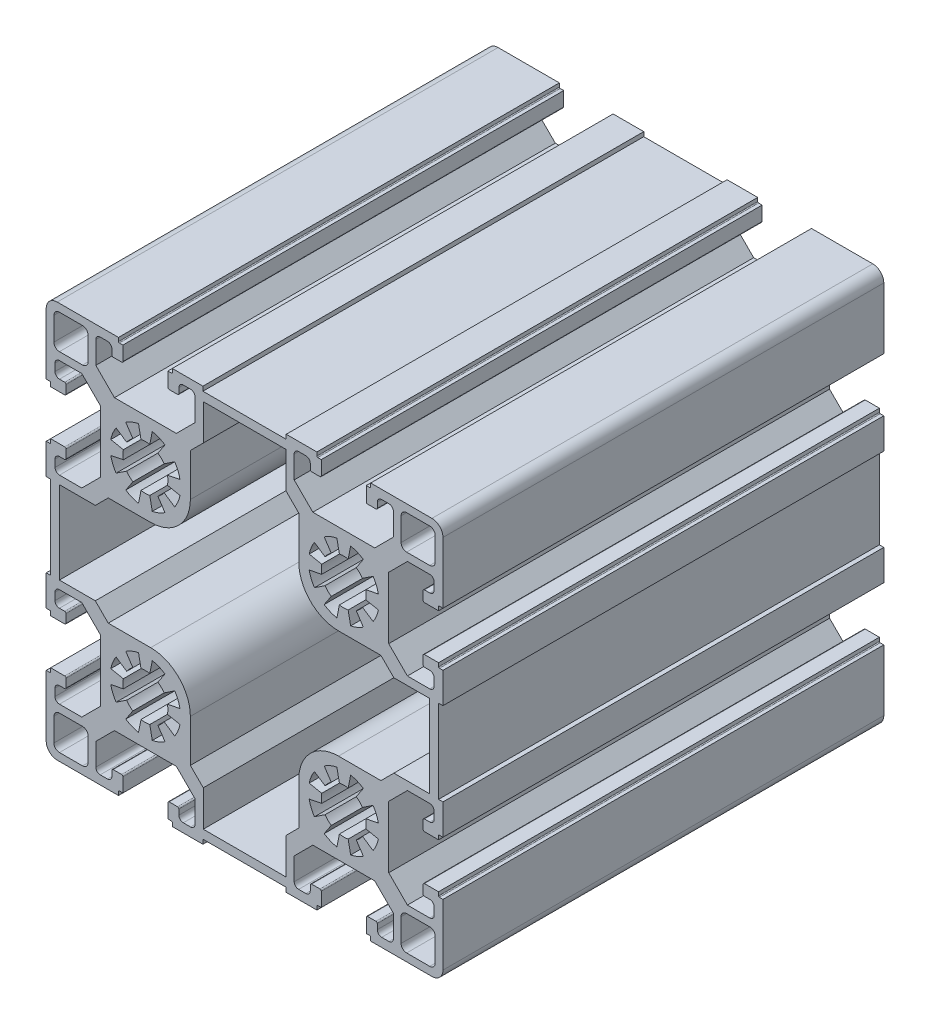
SolidWorks part; units mm, degrees
ref_plane "前视基准面" through (0, 0, 0) normal (0, 0, 1) x (1, 0, 0)
ref_plane "上视基准面" through (0, 0, 0) normal (0, 1, 0) x (1, 0, 0)
ref_plane "右视基准面" through (0, 0, 0) normal (1, 0, 0) x (0, 0, -1)
sketch "草图1" plane through (0, 0, 0) normal (0, 0, 1) x (1, 0, 0)
  line L0 (-29.0828, 43.3346) -> (-42.9828, 43.3346)
  line L1 (-45.4828, 40.8346) -> (-45.4828, 26.9346)
  line L2 (-28.0828, 42.3346) -> (-28.0828, 39.1346)
  line L3 (-28.3828, 38.8346) -> (-30.2828, 38.8346)
  line L4 (-30.5828, 39.1346) -> (-30.5828, 40.3346)
  line L5 (-31.5828, 41.3346) -> (-33.2328, 41.3346)
  line L6 (-34.2328, 40.3346) -> (-34.2328, 35.2666)
  line L7 (-42.4828, 33.8346) -> (-37.2328, 33.8346)
  line L8 (-35.9828, 35.0846) -> (-35.9828, 40.3346)
  line L9 (-37.2328, 41.5846) -> (-42.4828, 41.5846)
  line L10 (-43.7328, 40.3346) -> (-43.7328, 35.0846)
  line L11 (-37.4148, 32.0846) -> (-42.4828, 32.0846)
  line L12 (-43.4828, 31.0846) -> (-43.4828, 29.4346)
  line L13 (-42.4828, 28.4346) -> (-41.2828, 28.4346)
  line L14 (-40.9828, 28.1346) -> (-40.9828, 26.2346)
  line L15 (-41.2828, 25.9346) -> (-44.4828, 25.9346)
  line L16 (-28.0828, 42.3346) -> (-28.8828, 42.3346)
  line L17 (-29.0828, 42.5346) -> (-29.0828, 43.3346)
  line L18 (-45.4828, 26.9346) -> (-44.6828, 26.9346)
  line L19 (-44.4828, 26.7346) -> (-44.4828, 25.9346)
  line L20 (-17.8828, 42.3346) -> (-17.8828, 39.1346)
  line L21 (-17.5828, 38.8346) -> (-15.6828, 38.8346)
  line L22 (-15.3828, 39.1346) -> (-15.3828, 40.3346)
  line L23 (-14.3828, 41.3346) -> (-12.7328, 41.3346)
  line L24 (-11.7328, 40.3346) -> (-11.7328, 35.2666)
  line L25 (-17.8828, 42.3346) -> (-17.0828, 42.3346)
  line L26 (-16.8828, 42.5346) -> (-16.8828, 43.3346)
  line L27 (-37.4148, 9.5846) -> (-42.4828, 9.5846)
  line L28 (-43.4828, 10.5846) -> (-43.4828, 12.2346)
  line L29 (-42.4828, 13.2346) -> (-41.2828, 13.2346)
  line L30 (-40.9828, 13.5346) -> (-40.9828, 15.4346)
  line L31 (-41.2828, 15.7346) -> (-44.4828, 15.7346)
  line L32 (-45.4828, 14.7346) -> (-44.6828, 14.7346)
  line L33 (-44.4828, 14.9346) -> (-44.4828, 15.7346)
  line L34 (-27.4274, 14.1828) -> (-25.8162, 16.5941)
  line L35 (-24.5435, 12.9883) -> (-23.9778, 15.8326)
  line L36 (-21.4221, 12.9883) -> (-21.9878, 15.8326)
  line L37 (-18.5382, 14.1828) -> (-20.1494, 16.5941)
  line L38 (-16.3311, 16.39) -> (-18.7423, 18.0012)
  line L39 (-15.1365, 19.2738) -> (-17.9808, 19.8396)
  line L40 (-15.1365, 22.3953) -> (-17.9808, 21.8295)
  line L41 (-16.3311, 25.2791) -> (-18.7423, 23.668)
  line L42 (-18.5382, 27.4863) -> (-20.1494, 25.0751)
  line L43 (-21.4221, 28.6809) -> (-21.9878, 25.8366)
  line L44 (-24.5435, 28.6809) -> (-23.9778, 25.8366)
  line L45 (-27.4274, 27.4863) -> (-25.8162, 25.0751)
  line L46 (-29.6346, 25.2791) -> (-27.2233, 23.668)
  line L47 (-30.8291, 22.3953) -> (-27.9848, 21.8295)
  line L48 (-30.8291, 19.2738) -> (-27.9848, 19.8396)
  line L49 (-29.6346, 16.39) -> (-27.2233, 18.0012)
  line L51 (-15.9648, 31.0346) -> (-30.0008, 31.0346)
  line L52 (-33.1828, 27.8526) -> (-33.1828, 13.8166)
  line L53 (-34.2328, 35.2666) -> (-30.0008, 31.0346)
  line L54 (-37.4148, 32.0846) -> (-33.1828, 27.8526)
  line L55 (-11.7328, 35.2666) -> (-15.9648, 31.0346)
  line L56 (-37.4148, 9.5846) -> (-33.1828, 13.8166)
  line L57 (16.9172, 42.3346) -> (16.9172, 39.1346)
  line L58 (16.6172, 38.8346) -> (14.7172, 38.8346)
  line L59 (14.4172, 39.1346) -> (14.4172, 40.3346)
  line L60 (13.4172, 41.3346) -> (11.7672, 41.3346)
  line L61 (10.7672, 40.3346) -> (10.7672, 35.2666)
  line L62 (16.9172, 42.3346) -> (16.1172, 42.3346)
  line L63 (15.9172, 42.5346) -> (15.9172, 43.3346)
  line L64 (28.1172, 43.3346) -> (42.0172, 43.3346)
  line L65 (44.5172, 40.8346) -> (44.5172, 26.9346)
  line L66 (27.1172, 42.3346) -> (27.1172, 39.1346)
  line L67 (27.4172, 38.8346) -> (29.3172, 38.8346)
  line L68 (29.6172, 39.1346) -> (29.6172, 40.3346)
  line L69 (30.6172, 41.3346) -> (32.2672, 41.3346)
  line L70 (33.2672, 40.3346) -> (33.2672, 35.2666)
  line L71 (41.5172, 33.8346) -> (36.2672, 33.8346)
  line L72 (36.2672, 41.5846) -> (41.5172, 41.5846)
  line L73 (42.7672, 40.3346) -> (42.7672, 35.0846)
  line L74 (36.4492, 32.0846) -> (41.5172, 32.0846)
  line L75 (42.5172, 31.0846) -> (42.5172, 29.4346)
  line L76 (41.5172, 28.4346) -> (40.3172, 28.4346)
  line L77 (40.0172, 28.1346) -> (40.0172, 26.2346)
  line L78 (40.3172, 25.9346) -> (43.5172, 25.9346)
  line L79 (27.1172, 42.3346) -> (27.9172, 42.3346)
  line L80 (28.1172, 42.5346) -> (28.1172, 43.3346)
  line L81 (44.5172, 26.9346) -> (43.7172, 26.9346)
  line L82 (43.5172, 26.7346) -> (43.5172, 25.9346)
  line L83 (36.4492, 9.5846) -> (41.5172, 9.5846)
  line L84 (42.5172, 10.5846) -> (42.5172, 12.2346)
  line L85 (41.5172, 13.2346) -> (40.3172, 13.2346)
  line L86 (40.0172, 13.5346) -> (40.0172, 15.4346)
  line L87 (40.3172, 15.7346) -> (43.5172, 15.7346)
  line L88 (44.5172, 14.7346) -> (43.7172, 14.7346)
  line L89 (43.5172, 14.9346) -> (43.5172, 15.7346)
  line L90 (17.5726, 14.1828) -> (19.1838, 16.5941)
  line L91 (20.4565, 12.9883) -> (21.0222, 15.8326)
  line L92 (23.5779, 12.9883) -> (23.0122, 15.8326)
  line L93 (26.4618, 14.1828) -> (24.8506, 16.5941)
  line L94 (28.6689, 16.39) -> (26.2577, 18.0012)
  line L95 (29.8635, 19.2738) -> (27.0192, 19.8396)
  line L96 (29.8635, 22.3953) -> (27.0192, 21.8295)
  line L97 (28.6689, 25.2791) -> (26.2577, 23.668)
  line L98 (26.4618, 27.4863) -> (24.8506, 25.0751)
  line L99 (23.5779, 28.6809) -> (23.0122, 25.8366)
  line L100 (20.4565, 28.6809) -> (21.0222, 25.8366)
  line L101 (17.5726, 27.4863) -> (19.1838, 25.0751)
  line L102 (15.3654, 25.2791) -> (17.7767, 23.668)
  line L103 (14.1709, 22.3953) -> (17.0152, 21.8295)
  line L104 (14.1709, 19.2738) -> (17.0152, 19.8396)
  line L105 (15.3654, 16.39) -> (17.7767, 18.0012)
  line L106 (32.2172, 13.8166) -> (32.2172, 27.8526)
  line L107 (29.0352, 31.0346) -> (14.9992, 31.0346)
  line L109 (10.7672, 35.2666) -> (14.9992, 31.0346)
  line L110 (33.2672, 35.2666) -> (29.0352, 31.0346)
  line L111 (36.4492, 32.0846) -> (32.2172, 27.8526)
  line L112 (36.4492, 9.5846) -> (32.2172, 13.8166)
  line L113 (-16.8828, 43.3346) -> (-9.9328, 43.3346)
  line L114 (-9.9328, 42.3346) -> (8.9672, 42.3346)
  line L115 (-9.8534, 40.3346) -> (8.8878, 40.3346)
  line L116 (-9.8534, 32.1962) -> (-12.7828, 29.2668)
  line L117 (15.9172, 43.3346) -> (8.9672, 43.3346)
  line L118 (8.8878, 32.1962) -> (11.8172, 29.2668)
  line L119 (8.9672, 42.3346) -> (8.9672, 43.3346)
  line L120 (-9.9328, 42.3346) -> (-9.9328, 43.3346)
  line L122 (11.8172, 29.2668) -> (11.8172, 19.6346)
  line L123 (-9.8534, 32.1962) -> (-9.8534, 40.3346)
  line L124 (8.8878, 32.1962) -> (8.8878, 40.3346)
  line L125 (-29.0828, -46.6654) -> (-42.9828, -46.6654)
  line L126 (-45.4828, -44.1654) -> (-45.4828, -30.2654)
  line L127 (-28.0828, -45.6654) -> (-28.0828, -42.4654)
  line L128 (-28.3828, -42.1654) -> (-30.2828, -42.1654)
  line L129 (-30.5828, -42.4654) -> (-30.5828, -43.6654)
  line L130 (-31.5828, -44.6654) -> (-33.2328, -44.6654)
  line L131 (-34.2328, -43.6654) -> (-34.2328, -38.5974)
  line L132 (-42.4828, -37.1654) -> (-37.2328, -37.1654)
  line L133 (-35.9828, -38.4154) -> (-35.9828, -43.6654)
  line L134 (-37.2328, -44.9154) -> (-42.4828, -44.9154)
  line L135 (-43.7328, -43.6654) -> (-43.7328, -38.4154)
  line L136 (-37.4148, -35.4154) -> (-42.4828, -35.4154)
  line L137 (-43.4828, -34.4154) -> (-43.4828, -32.7654)
  line L138 (-42.4828, -31.7654) -> (-41.2828, -31.7654)
  line L139 (-40.9828, -31.4654) -> (-40.9828, -29.5654)
  line L140 (-41.2828, -29.2654) -> (-44.4828, -29.2654)
  line L141 (-28.0828, -45.6654) -> (-28.8828, -45.6654)
  line L142 (-29.0828, -45.8654) -> (-29.0828, -46.6654)
  line L143 (-45.4828, -30.2654) -> (-44.6828, -30.2654)
  line L144 (-44.4828, -30.0654) -> (-44.4828, -29.2654)
  line L145 (-17.8828, -45.6654) -> (-17.8828, -42.4654)
  line L146 (-17.5828, -42.1654) -> (-15.6828, -42.1654)
  line L147 (-15.3828, -42.4654) -> (-15.3828, -43.6654)
  line L148 (-14.3828, -44.6654) -> (-12.7328, -44.6654)
  line L149 (-11.7328, -43.6654) -> (-11.7328, -38.5974)
  line L150 (-17.8828, -45.6654) -> (-17.0828, -45.6654)
  line L151 (-16.8828, -45.8654) -> (-16.8828, -46.6654)
  line L152 (-37.4148, -12.9154) -> (-42.4828, -12.9154)
  line L153 (-43.4828, -13.9154) -> (-43.4828, -15.5654)
  line L154 (-42.4828, -16.5654) -> (-41.2828, -16.5654)
  line L155 (-40.9828, -16.8654) -> (-40.9828, -18.7654)
  line L156 (-41.2828, -19.0654) -> (-44.4828, -19.0654)
  line L157 (-45.4828, -18.0654) -> (-44.6828, -18.0654)
  line L158 (-44.4828, -18.2654) -> (-44.4828, -19.0654)
  line L159 (-27.4274, -17.5137) -> (-25.8162, -19.9249)
  line L160 (-24.5435, -16.3191) -> (-23.9778, -19.1634)
  line L161 (-21.4221, -16.3191) -> (-21.9878, -19.1634)
  line L162 (-18.5382, -17.5137) -> (-20.1494, -19.9249)
  line L163 (-16.3311, -19.7209) -> (-18.7423, -21.332)
  line L164 (-15.1365, -22.6047) -> (-17.9808, -23.1705)
  line L165 (-15.1365, -25.7262) -> (-17.9808, -25.1604)
  line L166 (-16.3311, -28.61) -> (-18.7423, -26.9988)
  line L167 (-18.5382, -30.8172) -> (-20.1494, -28.4059)
  line L168 (-21.4221, -32.0117) -> (-21.9878, -29.1674)
  line L169 (-24.5435, -32.0117) -> (-23.9778, -29.1674)
  line L170 (-27.4274, -30.8172) -> (-25.8162, -28.4059)
  line L171 (-29.6346, -28.61) -> (-27.2233, -26.9988)
  line L172 (-30.8291, -25.7262) -> (-27.9848, -25.1604)
  line L173 (-30.8291, -22.6047) -> (-27.9848, -23.1705)
  line L174 (-29.6346, -19.7209) -> (-27.2233, -21.332)
  line L176 (-15.9648, -34.3654) -> (-30.0008, -34.3654)
  line L177 (-33.1828, -31.1834) -> (-33.1828, -17.1474)
  line L178 (-34.2328, -38.5974) -> (-30.0008, -34.3654)
  line L179 (-37.4148, -35.4154) -> (-33.1828, -31.1834)
  line L180 (-11.7328, -38.5974) -> (-15.9648, -34.3654)
  line L181 (-37.4148, -12.9154) -> (-33.1828, -17.1474)
  line L182 (16.9172, -45.6654) -> (16.9172, -42.4654)
  line L183 (16.6172, -42.1654) -> (14.7172, -42.1654)
  line L184 (14.4172, -42.4654) -> (14.4172, -43.6654)
  line L185 (13.4172, -44.6654) -> (11.7672, -44.6654)
  line L186 (10.7672, -43.6654) -> (10.7672, -38.5974)
  line L187 (16.9172, -45.6654) -> (16.1172, -45.6654)
  line L188 (15.9172, -45.8654) -> (15.9172, -46.6654)
  line L189 (28.1172, -46.6654) -> (42.0172, -46.6654)
  line L190 (44.5172, -44.1654) -> (44.5172, -30.2654)
  line L191 (27.1172, -45.6654) -> (27.1172, -42.4654)
  line L192 (27.4172, -42.1654) -> (29.3172, -42.1654)
  line L193 (29.6172, -42.4654) -> (29.6172, -43.6654)
  line L194 (30.6172, -44.6654) -> (32.2672, -44.6654)
  line L195 (33.2672, -43.6654) -> (33.2672, -38.5974)
  line L196 (41.5172, -37.1654) -> (36.2672, -37.1654)
  line L197 (35.0172, -38.4154) -> (35.0172, -43.6654)
  line L198 (36.2672, -44.9154) -> (41.5172, -44.9154)
  line L199 (42.7672, -43.6654) -> (42.7672, -38.4154)
  line L200 (36.4492, -35.4154) -> (41.5172, -35.4154)
  line L201 (42.5172, -34.4154) -> (42.5172, -32.7654)
  line L202 (41.5172, -31.7654) -> (40.3172, -31.7654)
  line L203 (40.0172, -31.4654) -> (40.0172, -29.5654)
  line L204 (40.3172, -29.2654) -> (43.5172, -29.2654)
  line L205 (27.1172, -45.6654) -> (27.9172, -45.6654)
  line L206 (28.1172, -45.8654) -> (28.1172, -46.6654)
  line L207 (44.5172, -30.2654) -> (43.7172, -30.2654)
  line L208 (43.5172, -30.0654) -> (43.5172, -29.2654)
  line L209 (36.4492, -12.9154) -> (41.5172, -12.9154)
  line L210 (42.5172, -13.9154) -> (42.5172, -15.5654)
  line L211 (41.5172, -16.5654) -> (40.3172, -16.5654)
  line L212 (40.0172, -16.8654) -> (40.0172, -18.7654)
  line L213 (40.3172, -19.0654) -> (43.5172, -19.0654)
  line L214 (44.5172, -18.0654) -> (43.7172, -18.0654)
  line L215 (43.5172, -18.2654) -> (43.5172, -19.0654)
  line L216 (17.5726, -17.5137) -> (19.1838, -19.9249)
  line L217 (20.4565, -16.3191) -> (21.0222, -19.1634)
  line L218 (23.5779, -16.3191) -> (23.0122, -19.1634)
  line L219 (26.4618, -17.5137) -> (24.8506, -19.9249)
  line L220 (28.6689, -19.7209) -> (26.2577, -21.332)
  line L221 (29.8635, -22.6047) -> (27.0192, -23.1705)
  line L222 (29.8635, -25.7262) -> (27.0192, -25.1604)
  line L223 (28.6689, -28.61) -> (26.2577, -26.9988)
  line L224 (26.4618, -30.8172) -> (24.8506, -28.4059)
  line L225 (23.5779, -32.0117) -> (23.0122, -29.1674)
  line L226 (20.4565, -32.0117) -> (21.0222, -29.1674)
  line L227 (17.5726, -30.8172) -> (19.1838, -28.4059)
  line L228 (15.3654, -28.61) -> (17.7767, -26.9988)
  line L229 (14.1709, -25.7262) -> (17.0152, -25.1604)
  line L230 (14.1709, -22.6047) -> (17.0152, -23.1705)
  line L231 (15.3654, -19.7209) -> (17.7767, -21.332)
  line L232 (32.2172, -17.1474) -> (32.2172, -31.1834)
  line L233 (29.0352, -34.3654) -> (14.9992, -34.3654)
  line L235 (10.7672, -38.5974) -> (14.9992, -34.3654)
  line L236 (33.2672, -38.5974) -> (29.0352, -34.3654)
  line L237 (36.4492, -35.4154) -> (32.2172, -31.1834)
  line L238 (36.4492, -12.9154) -> (32.2172, -17.1474)
  line L239 (-16.8828, -46.6654) -> (-9.9328, -46.6654)
  line L240 (-9.9328, -45.6654) -> (8.9672, -45.6654)
  line L241 (-9.8534, -43.6654) -> (8.8878, -43.6654)
  line L242 (-9.8534, -35.527) -> (-12.7828, -32.5977)
  line L243 (15.9172, -46.6654) -> (8.9672, -46.6654)
  line L244 (8.8878, -35.527) -> (11.8172, -32.5977)
  line L245 (8.9672, -45.6654) -> (8.9672, -46.6654)
  line L246 (-9.9328, -45.6654) -> (-9.9328, -46.6654)
  line L247 (-12.7828, -32.5977) -> (-12.7828, -22.9654)
  line L249 (-9.8534, -35.527) -> (-9.8534, -43.6654)
  line L250 (8.8878, -35.527) -> (8.8878, -43.6654)
  line L251 (-45.4828, 14.7346) -> (-45.4828, 7.7846)
  line L252 (-44.4828, 7.7846) -> (-44.4828, -11.1154)
  line L253 (-42.4828, 7.7052) -> (-42.4828, -11.0361)
  line L254 (-34.3444, 7.7052) -> (-31.415, 10.6346)
  line L255 (-45.4828, -18.0654) -> (-45.4828, -11.1154)
  line L256 (-34.3444, -11.0361) -> (-31.415, -13.9654)
  line L257 (-44.4828, -11.1154) -> (-45.4828, -11.1154)
  line L258 (-44.4828, 7.7846) -> (-45.4828, 7.7846)
  line L259 (-31.415, 10.6346) -> (-21.7828, 10.6346)
  line L260 (-31.415, -13.9654) -> (-21.7828, -13.9654)
  line L261 (-34.3444, 7.7052) -> (-42.4828, 7.7052)
  line L262 (-34.3444, -11.0361) -> (-42.4828, -11.0361)
  line L263 (44.5172, 14.7346) -> (44.5172, 7.7846)
  line L264 (43.5172, 7.7846) -> (43.5172, -11.1154)
  line L265 (41.5172, 7.7052) -> (41.5172, -11.0361)
  line L266 (33.3788, 7.7052) -> (30.4494, 10.6346)
  line L267 (44.5172, -18.0654) -> (44.5172, -11.1154)
  line L268 (33.3788, -11.0361) -> (30.4494, -13.9654)
  line L269 (43.5172, -11.1154) -> (44.5172, -11.1154)
  line L270 (43.5172, 7.7846) -> (44.5172, 7.7846)
  line L271 (30.4494, 10.6346) -> (20.8172, 10.6346)
  line L272 (30.4494, -13.9654) -> (20.8172, -13.9654)
  line L273 (33.3788, 7.7052) -> (41.5172, 7.7052)
  line L274 (33.3788, -11.0361) -> (41.5172, -11.0361)
  line L357 (-12.7828, 19.6346) -> (-12.7828, 29.2668)
  line L371 (11.8172, -22.9654) -> (11.8172, -32.5977)
  line L543 (35.0172, 35.0846) -> (35.0172, 40.3346)
  arc A0 (-42.9828, 43.3346) -> (-45.4828, 40.8346) centre (-42.9828, 40.8346) ccw
  arc A1 (-28.3828, 38.8346) -> (-28.0828, 39.1346) centre (-28.3828, 39.1346) ccw
  arc A2 (-30.5828, 39.1346) -> (-30.2828, 38.8346) centre (-30.2828, 39.1346) ccw
  arc A3 (-30.5828, 40.3346) -> (-31.5828, 41.3346) centre (-31.5828, 40.3346) ccw
  arc A4 (-33.2328, 41.3346) -> (-34.2328, 40.3346) centre (-33.2328, 40.3346) ccw
  arc A5 (-37.2328, 33.8346) -> (-35.9828, 35.0846) centre (-37.2328, 35.0846) ccw
  arc A6 (-35.9828, 40.3346) -> (-37.2328, 41.5846) centre (-37.2328, 40.3346) ccw
  arc A7 (-42.4828, 41.5846) -> (-43.7328, 40.3346) centre (-42.4828, 40.3346) ccw
  arc A8 (-43.7328, 35.0846) -> (-42.4828, 33.8346) centre (-42.4828, 35.0846) ccw
  arc A9 (-42.4828, 32.0846) -> (-43.4828, 31.0846) centre (-42.4828, 31.0846) ccw
  arc A10 (-43.4828, 29.4346) -> (-42.4828, 28.4346) centre (-42.4828, 29.4346) ccw
  arc A11 (-40.9828, 28.1346) -> (-41.2828, 28.4346) centre (-41.2828, 28.1346) ccw
  arc A12 (-41.2828, 25.9346) -> (-40.9828, 26.2346) centre (-41.2828, 26.2346) ccw
  arc A13 (-29.0828, 42.5346) -> (-28.8828, 42.3346) centre (-28.8828, 42.5346) ccw
  arc A14 (-44.4828, 26.7346) -> (-44.6828, 26.9346) centre (-44.6828, 26.7346) ccw
  arc A15 (-23.9778, 15.8326) -> (-21.9878, 15.8326) centre (-22.9828, 20.8346) ccw
  arc A16 (-20.1494, 16.5941) -> (-18.7423, 18.0012) centre (-22.9828, 20.8346) ccw
  arc A17 (-17.9808, 19.8396) -> (-17.9808, 21.8295) centre (-22.9828, 20.8346) ccw
  arc A18 (-18.7423, 23.668) -> (-20.1494, 25.0751) centre (-22.9828, 20.8346) ccw
  arc A19 (-21.9878, 25.8366) -> (-23.9778, 25.8366) centre (-22.9828, 20.8346) ccw
  arc A20 (-25.8162, 25.0751) -> (-27.2233, 23.668) centre (-22.9828, 20.8346) ccw
  arc A21 (-27.9848, 21.8295) -> (-27.9848, 19.8396) centre (-22.9828, 20.8346) ccw
  arc A22 (-27.2233, 18.0012) -> (-25.8162, 16.5941) centre (-22.9828, 20.8346) ccw
  arc A23 (-27.4274, 14.1828) -> (-24.5435, 12.9883) centre (-22.9828, 20.8346) ccw
  arc A24 (-21.4221, 12.9883) -> (-18.5382, 14.1828) centre (-22.9828, 20.8346) ccw
  arc A25 (-16.3311, 16.39) -> (-15.1365, 19.2738) centre (-22.9828, 20.8346) ccw
  arc A26 (-15.1365, 22.3953) -> (-16.3311, 25.2791) centre (-22.9828, 20.8346) ccw
  arc A27 (-18.5382, 27.4863) -> (-21.4221, 28.6809) centre (-22.9828, 20.8346) ccw
  arc A28 (-24.5435, 28.6809) -> (-27.4274, 27.4863) centre (-22.9828, 20.8346) ccw
  arc A29 (-29.6346, 25.2791) -> (-30.8291, 22.3953) centre (-22.9828, 20.8346) ccw
  arc A30 (-30.8291, 19.2738) -> (-29.6346, 16.39) centre (-22.9828, 20.8346) ccw
  arc A31 (-17.8828, 39.1346) -> (-17.5828, 38.8346) centre (-17.5828, 39.1346) ccw
  arc A32 (-15.6828, 38.8346) -> (-15.3828, 39.1346) centre (-15.6828, 39.1346) ccw
  arc A33 (-14.3828, 41.3346) -> (-15.3828, 40.3346) centre (-14.3828, 40.3346) ccw
  arc A34 (-11.7328, 40.3346) -> (-12.7328, 41.3346) centre (-12.7328, 40.3346) ccw
  arc A35 (-17.0828, 42.3346) -> (-16.8828, 42.5346) centre (-17.0828, 42.5346) ccw
  arc A36 (-43.4828, 10.5846) -> (-42.4828, 9.5846) centre (-42.4828, 10.5846) ccw
  arc A37 (-42.4828, 13.2346) -> (-43.4828, 12.2346) centre (-42.4828, 12.2346) ccw
  arc A38 (-41.2828, 13.2346) -> (-40.9828, 13.5346) centre (-41.2828, 13.5346) ccw
  arc A39 (-40.9828, 15.4346) -> (-41.2828, 15.7346) centre (-41.2828, 15.4346) ccw
  arc A40 (-44.6828, 14.7346) -> (-44.4828, 14.9346) centre (-44.6828, 14.9346) ccw
  arc A41 (16.6172, 38.8346) -> (16.9172, 39.1346) centre (16.6172, 39.1346) ccw
  arc A42 (14.4172, 39.1346) -> (14.7172, 38.8346) centre (14.7172, 39.1346) ccw
  arc A43 (14.4172, 40.3346) -> (13.4172, 41.3346) centre (13.4172, 40.3346) ccw
  arc A44 (11.7672, 41.3346) -> (10.7672, 40.3346) centre (11.7672, 40.3346) ccw
  arc A45 (15.9172, 42.5346) -> (16.1172, 42.3346) centre (16.1172, 42.5346) ccw
  arc A46 (21.0222, 15.8326) -> (23.0122, 15.8326) centre (22.0172, 20.8346) ccw
  arc A47 (24.8506, 16.5941) -> (26.2577, 18.0012) centre (22.0172, 20.8346) ccw
  arc A48 (27.0192, 19.8396) -> (27.0192, 21.8295) centre (22.0172, 20.8346) ccw
  arc A49 (26.2577, 23.668) -> (24.8506, 25.0751) centre (22.0172, 20.8346) ccw
  arc A50 (23.0122, 25.8366) -> (21.0222, 25.8366) centre (22.0172, 20.8346) ccw
  arc A51 (19.1838, 25.0751) -> (17.7767, 23.668) centre (22.0172, 20.8346) ccw
  arc A52 (17.0152, 21.8295) -> (17.0152, 19.8396) centre (22.0172, 20.8346) ccw
  arc A53 (17.7767, 18.0012) -> (19.1838, 16.5941) centre (22.0172, 20.8346) ccw
  arc A54 (17.5726, 14.1828) -> (20.4565, 12.9883) centre (22.0172, 20.8346) ccw
  arc A55 (23.5779, 12.9883) -> (26.4618, 14.1828) centre (22.0172, 20.8346) ccw
  arc A56 (28.6689, 16.39) -> (29.8635, 19.2738) centre (22.0172, 20.8346) ccw
  arc A57 (29.8635, 22.3953) -> (28.6689, 25.2791) centre (22.0172, 20.8346) ccw
  arc A58 (26.4618, 27.4863) -> (23.5779, 28.6809) centre (22.0172, 20.8346) ccw
  arc A59 (20.4565, 28.6809) -> (17.5726, 27.4863) centre (22.0172, 20.8346) ccw
  arc A60 (15.3654, 25.2791) -> (14.1709, 22.3953) centre (22.0172, 20.8346) ccw
  arc A61 (14.1709, 19.2738) -> (15.3654, 16.39) centre (22.0172, 20.8346) ccw
  arc A62 (44.5172, 40.8346) -> (42.0172, 43.3346) centre (42.0172, 40.8346) ccw
  arc A63 (27.1172, 39.1346) -> (27.4172, 38.8346) centre (27.4172, 39.1346) ccw
  arc A64 (29.3172, 38.8346) -> (29.6172, 39.1346) centre (29.3172, 39.1346) ccw
  arc A65 (30.6172, 41.3346) -> (29.6172, 40.3346) centre (30.6172, 40.3346) ccw
  arc A66 (33.2672, 40.3346) -> (32.2672, 41.3346) centre (32.2672, 40.3346) ccw
  arc A67 (35.0172, 35.0846) -> (36.2672, 33.8346) centre (36.2672, 35.0846) ccw
  arc A68 (36.2672, 41.5846) -> (35.0172, 40.3346) centre (36.2672, 40.3346) ccw
  arc A69 (42.7672, 40.3346) -> (41.5172, 41.5846) centre (41.5172, 40.3346) ccw
  arc A70 (41.5172, 33.8346) -> (42.7672, 35.0846) centre (41.5172, 35.0846) ccw
  arc A71 (42.5172, 31.0846) -> (41.5172, 32.0846) centre (41.5172, 31.0846) ccw
  arc A72 (41.5172, 28.4346) -> (42.5172, 29.4346) centre (41.5172, 29.4346) ccw
  arc A73 (40.3172, 28.4346) -> (40.0172, 28.1346) centre (40.3172, 28.1346) ccw
  arc A74 (40.0172, 26.2346) -> (40.3172, 25.9346) centre (40.3172, 26.2346) ccw
  arc A75 (27.9172, 42.3346) -> (28.1172, 42.5346) centre (27.9172, 42.5346) ccw
  arc A76 (43.7172, 26.9346) -> (43.5172, 26.7346) centre (43.7172, 26.7346) ccw
  arc A77 (41.5172, 9.5846) -> (42.5172, 10.5846) centre (41.5172, 10.5846) ccw
  arc A78 (42.5172, 12.2346) -> (41.5172, 13.2346) centre (41.5172, 12.2346) ccw
  arc A79 (40.0172, 13.5346) -> (40.3172, 13.2346) centre (40.3172, 13.5346) ccw
  arc A80 (40.3172, 15.7346) -> (40.0172, 15.4346) centre (40.3172, 15.4346) ccw
  arc A81 (43.5172, 14.9346) -> (43.7172, 14.7346) centre (43.7172, 14.9346) ccw
  arc A82 (-21.7828, 10.6346) -> (-12.7828, 19.6346) centre (-21.7828, 19.6346) ccw
  arc A83 (-45.4828, -44.1654) -> (-42.9828, -46.6654) centre (-42.9828, -44.1654) ccw
  arc A84 (-28.0828, -42.4654) -> (-28.3828, -42.1654) centre (-28.3828, -42.4654) ccw
  arc A85 (-30.2828, -42.1654) -> (-30.5828, -42.4654) centre (-30.2828, -42.4654) ccw
  arc A86 (-31.5828, -44.6654) -> (-30.5828, -43.6654) centre (-31.5828, -43.6654) ccw
  arc A87 (-34.2328, -43.6654) -> (-33.2328, -44.6654) centre (-33.2328, -43.6654) ccw
  arc A88 (-35.9828, -38.4154) -> (-37.2328, -37.1654) centre (-37.2328, -38.4154) ccw
  arc A89 (-37.2328, -44.9154) -> (-35.9828, -43.6654) centre (-37.2328, -43.6654) ccw
  arc A90 (-43.7328, -43.6654) -> (-42.4828, -44.9154) centre (-42.4828, -43.6654) ccw
  arc A91 (-42.4828, -37.1654) -> (-43.7328, -38.4154) centre (-42.4828, -38.4154) ccw
  arc A92 (-43.4828, -34.4154) -> (-42.4828, -35.4154) centre (-42.4828, -34.4154) ccw
  arc A93 (-42.4828, -31.7654) -> (-43.4828, -32.7654) centre (-42.4828, -32.7654) ccw
  arc A94 (-41.2828, -31.7654) -> (-40.9828, -31.4654) centre (-41.2828, -31.4654) ccw
  arc A95 (-40.9828, -29.5654) -> (-41.2828, -29.2654) centre (-41.2828, -29.5654) ccw
  arc A96 (-28.8828, -45.6654) -> (-29.0828, -45.8654) centre (-28.8828, -45.8654) ccw
  arc A97 (-44.6828, -30.2654) -> (-44.4828, -30.0654) centre (-44.6828, -30.0654) ccw
  arc A98 (-21.9878, -19.1634) -> (-23.9778, -19.1634) centre (-22.9828, -24.1654) ccw
  arc A99 (-18.7423, -21.332) -> (-20.1494, -19.9249) centre (-22.9828, -24.1654) ccw
  arc A100 (-17.9808, -25.1604) -> (-17.9808, -23.1705) centre (-22.9828, -24.1654) ccw
  arc A101 (-20.1494, -28.4059) -> (-18.7423, -26.9988) centre (-22.9828, -24.1654) ccw
  arc A102 (-23.9778, -29.1674) -> (-21.9878, -29.1674) centre (-22.9828, -24.1654) ccw
  arc A103 (-27.2233, -26.9988) -> (-25.8162, -28.4059) centre (-22.9828, -24.1654) ccw
  arc A104 (-27.9848, -23.1705) -> (-27.9848, -25.1604) centre (-22.9828, -24.1654) ccw
  arc A105 (-25.8162, -19.9249) -> (-27.2233, -21.332) centre (-22.9828, -24.1654) ccw
  arc A106 (-24.5435, -16.3191) -> (-27.4274, -17.5137) centre (-22.9828, -24.1654) ccw
  arc A107 (-18.5382, -17.5137) -> (-21.4221, -16.3191) centre (-22.9828, -24.1654) ccw
  arc A108 (-15.1365, -22.6047) -> (-16.3311, -19.7209) centre (-22.9828, -24.1654) ccw
  arc A109 (-16.3311, -28.61) -> (-15.1365, -25.7262) centre (-22.9828, -24.1654) ccw
  arc A110 (-21.4221, -32.0117) -> (-18.5382, -30.8172) centre (-22.9828, -24.1654) ccw
  arc A111 (-27.4274, -30.8172) -> (-24.5435, -32.0117) centre (-22.9828, -24.1654) ccw
  arc A112 (-30.8291, -25.7262) -> (-29.6346, -28.61) centre (-22.9828, -24.1654) ccw
  arc A113 (-29.6346, -19.7209) -> (-30.8291, -22.6047) centre (-22.9828, -24.1654) ccw
  arc A114 (-17.5828, -42.1654) -> (-17.8828, -42.4654) centre (-17.5828, -42.4654) ccw
  arc A115 (-15.3828, -42.4654) -> (-15.6828, -42.1654) centre (-15.6828, -42.4654) ccw
  arc A116 (-15.3828, -43.6654) -> (-14.3828, -44.6654) centre (-14.3828, -43.6654) ccw
  arc A117 (-12.7328, -44.6654) -> (-11.7328, -43.6654) centre (-12.7328, -43.6654) ccw
  arc A118 (-16.8828, -45.8654) -> (-17.0828, -45.6654) centre (-17.0828, -45.8654) ccw
  arc A119 (-42.4828, -12.9154) -> (-43.4828, -13.9154) centre (-42.4828, -13.9154) ccw
  arc A120 (-43.4828, -15.5654) -> (-42.4828, -16.5654) centre (-42.4828, -15.5654) ccw
  arc A121 (-40.9828, -16.8654) -> (-41.2828, -16.5654) centre (-41.2828, -16.8654) ccw
  arc A122 (-41.2828, -19.0654) -> (-40.9828, -18.7654) centre (-41.2828, -18.7654) ccw
  arc A123 (-44.4828, -18.2654) -> (-44.6828, -18.0654) centre (-44.6828, -18.2654) ccw
  arc A124 (16.9172, -42.4654) -> (16.6172, -42.1654) centre (16.6172, -42.4654) ccw
  arc A125 (14.7172, -42.1654) -> (14.4172, -42.4654) centre (14.7172, -42.4654) ccw
  arc A126 (13.4172, -44.6654) -> (14.4172, -43.6654) centre (13.4172, -43.6654) ccw
  arc A127 (10.7672, -43.6654) -> (11.7672, -44.6654) centre (11.7672, -43.6654) ccw
  arc A128 (16.1172, -45.6654) -> (15.9172, -45.8654) centre (16.1172, -45.8654) ccw
  arc A129 (23.0122, -19.1634) -> (21.0222, -19.1634) centre (22.0172, -24.1654) ccw
  arc A130 (26.2577, -21.332) -> (24.8506, -19.9249) centre (22.0172, -24.1654) ccw
  arc A131 (27.0192, -25.1604) -> (27.0192, -23.1705) centre (22.0172, -24.1654) ccw
  arc A132 (24.8506, -28.4059) -> (26.2577, -26.9988) centre (22.0172, -24.1654) ccw
  arc A133 (21.0222, -29.1674) -> (23.0122, -29.1674) centre (22.0172, -24.1654) ccw
  arc A134 (17.7767, -26.9988) -> (19.1838, -28.4059) centre (22.0172, -24.1654) ccw
  arc A135 (17.0152, -23.1705) -> (17.0152, -25.1604) centre (22.0172, -24.1654) ccw
  arc A136 (19.1838, -19.9249) -> (17.7767, -21.332) centre (22.0172, -24.1654) ccw
  arc A137 (20.4565, -16.3191) -> (17.5726, -17.5137) centre (22.0172, -24.1654) ccw
  arc A138 (26.4618, -17.5137) -> (23.5779, -16.3191) centre (22.0172, -24.1654) ccw
  arc A139 (29.8635, -22.6047) -> (28.6689, -19.7209) centre (22.0172, -24.1654) ccw
  arc A140 (28.6689, -28.61) -> (29.8635, -25.7262) centre (22.0172, -24.1654) ccw
  arc A141 (23.5779, -32.0117) -> (26.4618, -30.8172) centre (22.0172, -24.1654) ccw
  arc A142 (17.5726, -30.8172) -> (20.4565, -32.0117) centre (22.0172, -24.1654) ccw
  arc A143 (14.1709, -25.7262) -> (15.3654, -28.61) centre (22.0172, -24.1654) ccw
  arc A144 (15.3654, -19.7209) -> (14.1709, -22.6047) centre (22.0172, -24.1654) ccw
  arc A145 (42.0172, -46.6654) -> (44.5172, -44.1654) centre (42.0172, -44.1654) ccw
  arc A146 (27.4172, -42.1654) -> (27.1172, -42.4654) centre (27.4172, -42.4654) ccw
  arc A147 (29.6172, -42.4654) -> (29.3172, -42.1654) centre (29.3172, -42.4654) ccw
  arc A148 (29.6172, -43.6654) -> (30.6172, -44.6654) centre (30.6172, -43.6654) ccw
  arc A149 (32.2672, -44.6654) -> (33.2672, -43.6654) centre (32.2672, -43.6654) ccw
  arc A150 (36.2672, -37.1654) -> (35.0172, -38.4154) centre (36.2672, -38.4154) ccw
  arc A151 (35.0172, -43.6654) -> (36.2672, -44.9154) centre (36.2672, -43.6654) ccw
  arc A152 (41.5172, -44.9154) -> (42.7672, -43.6654) centre (41.5172, -43.6654) ccw
  arc A153 (42.7672, -38.4154) -> (41.5172, -37.1654) centre (41.5172, -38.4154) ccw
  arc A154 (41.5172, -35.4154) -> (42.5172, -34.4154) centre (41.5172, -34.4154) ccw
  arc A155 (42.5172, -32.7654) -> (41.5172, -31.7654) centre (41.5172, -32.7654) ccw
  arc A156 (40.0172, -31.4654) -> (40.3172, -31.7654) centre (40.3172, -31.4654) ccw
  arc A157 (40.3172, -29.2654) -> (40.0172, -29.5654) centre (40.3172, -29.5654) ccw
  arc A158 (28.1172, -45.8654) -> (27.9172, -45.6654) centre (27.9172, -45.8654) ccw
  arc A159 (43.5172, -30.0654) -> (43.7172, -30.2654) centre (43.7172, -30.0654) ccw
  arc A160 (42.5172, -13.9154) -> (41.5172, -12.9154) centre (41.5172, -13.9154) ccw
  arc A161 (41.5172, -16.5654) -> (42.5172, -15.5654) centre (41.5172, -15.5654) ccw
  arc A162 (40.3172, -16.5654) -> (40.0172, -16.8654) centre (40.3172, -16.8654) ccw
  arc A163 (40.0172, -18.7654) -> (40.3172, -19.0654) centre (40.3172, -18.7654) ccw
  arc A164 (43.7172, -18.0654) -> (43.5172, -18.2654) centre (43.7172, -18.2654) ccw
  arc A165 (20.8172, -13.9654) -> (11.8172, -22.9654) centre (20.8172, -22.9654) ccw
  arc A166 (-12.7828, -22.9654) -> (-21.7828, -13.9654) centre (-21.7828, -22.9654) ccw
  arc A167 (11.8172, 19.6346) -> (20.8172, 10.6346) centre (20.8172, 19.6346) ccw
extrude "凸台-拉伸1" add sketch "草图1" along normal blind 100
